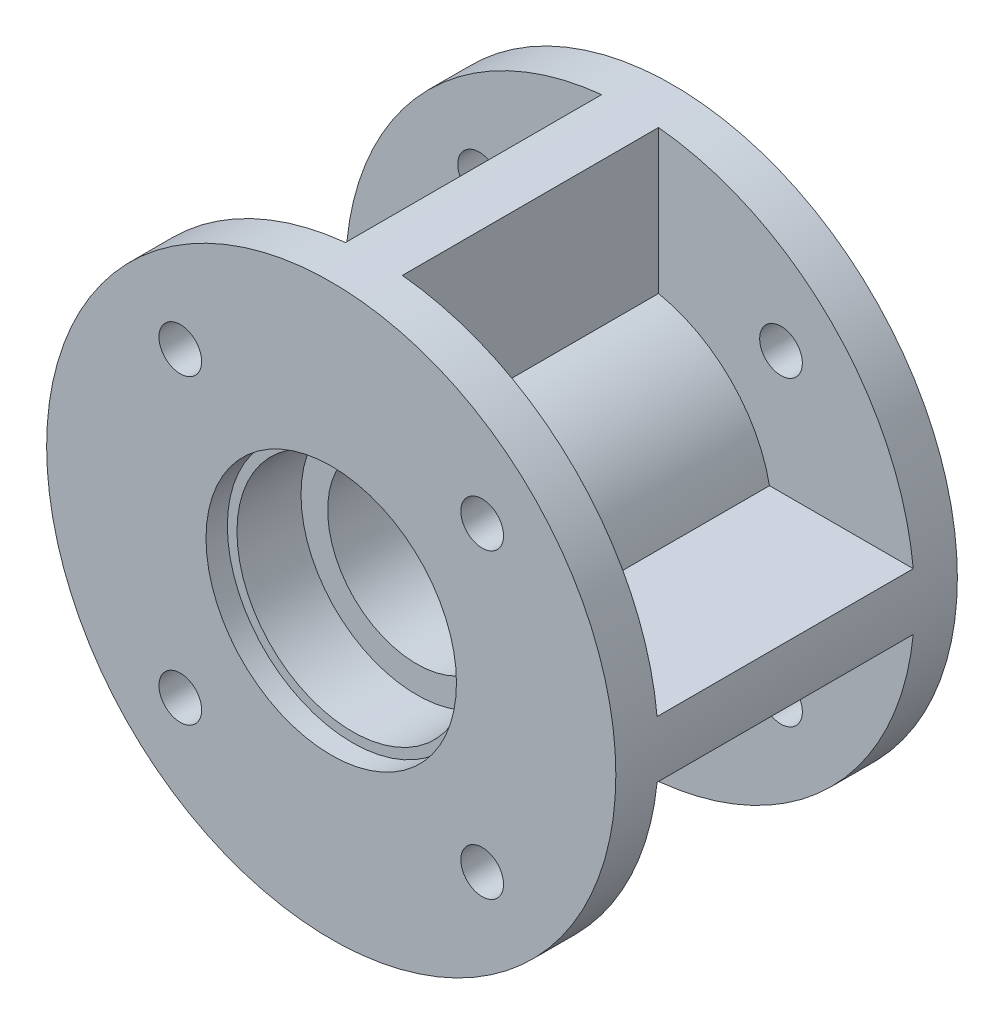
SolidWorks part; units mm, degrees
material "PLA Generic"
ref_plane "Front Plane" through (0, 0, 0) normal (0, 0, 1) x (1, 0, 0)
ref_plane "Top Plane" through (0, 0, 0) normal (0, 1, 0) x (1, 0, 0)
ref_plane "Right Plane" through (0, 0, 0) normal (1, 0, 0) x (0, 0, -1)
sketch "Sketch1" plane through (0, 0, 0) normal (0, 0, 1) x (1, 0, 0)
  circle A0 centre (0, 0) radius 12.5
  circle A1 centre (0, 0) radius 40
  dimension "D1" = 80
  dimension "D2" = 25
extrude "Boss-Extrude1" add sketch "Sketch1" along normal blind 6
sketch "Sketch2" plane through (0, 0, 6) normal (0, 0, 1) x (1, 0, 0)
  circle A0 centre (0, 0) radius 20
  circle A1 centre (0, 0) radius 12.5
  dimension "D1" = 40
extrude "Boss-Extrude2" add sketch "Sketch2" along normal blind 30
sketch "Sketch6" plane through (0, 0, 36) normal (0, 0, 1) x (1, 0, 0)
  circle A0 centre (0, 0) radius 20
  circle A1 centre (0, 0) radius 16.25
  dimension "D1" = 32.5
extrude "Boss-Extrude5" add sketch "Sketch6" along normal blind 12
sketch "Sketch8" plane through (0, 0, 6) normal (0, 0, 1) x (1, 0, 0)
  line L0 (4, -39.7995) -> (4, -19.5959)
  line L2 (39.7995, 4) -> (19.5959, 4)
  line L4 (19.5959, -4) -> (39.7995, -4)
  line L5 (20, 0) -> (40, 0) construction
  line L6 (-4, -19.5959) -> (-4, -39.7995)
  line L7 (-39.7995, -4) -> (-19.5959, -4)
  line L8 (-19.5959, 4) -> (-39.7995, 4)
  line L9 (-4, 39.7995) -> (-4, 19.5959)
  line L10 (4, 19.5959) -> (4, 39.7995)
  circle A0 centre (0, 0) radius 40 construction
  arc A1 (19.5959, -4) -> (19.5959, 4) centre (0, 0) ccw
  arc A2 (39.7995, -4) -> (39.7995, 4) centre (0, 0) ccw
  arc A3 (-4, -19.5959) -> (4, -19.5959) centre (0, 0) ccw
  arc A4 (-4, -39.7995) -> (4, -39.7995) centre (0, 0) ccw
  arc A5 (-19.5959, 4) -> (-19.5959, -4) centre (0, 0) ccw
  arc A6 (-39.7995, 4) -> (-39.7995, -4) centre (0, 0) ccw
  arc A7 (4, 19.5959) -> (-4, 19.5959) centre (0, 0) ccw
  arc A8 (4, 39.7995) -> (-4, 39.7995) centre (0, 0) ccw
  point P9 (40, 0)
  point P26 (0, 0)
  dimension "D1" = 4
extrude "Boss-Extrude6" add sketch "Sketch8" along normal up to surface (42 mm away) up to face at (20, 0, 48)
sketch "Sketch9" plane through (0, 0, 48) normal (0, 0, 1) x (1, 0, 0)
  circle A0 centre (0, 0) radius 17.6
  dimension "D1" = 35.2
extrude "Cut-Extrude1" cut sketch "Sketch9" against normal blind 3
sketch "Sketch11" plane through (0, 0, 48) normal (0, 0, 1) x (1, 0, 0)
  circle A0 centre (0, 0) radius 40
  circle A1 centre (0, 0) radius 20
extrude "Boss-Extrude14" add sketch "Sketch11" against normal blind 6 contours A0 | A1
sketch "Sketch12" plane through (0, 0, 0) normal (0, 0, -1) x (-1, 0, 0)
  line L0 (0, 0) -> (-54.2872, 0) construction
  line L1 (0, 0) -> (-21.2132, 21.2132) construction
  circle A0 centre (-21.2132, 21.2132) radius 3
  circle A1 centre (21.2132, 21.2132) radius 3
  circle A2 centre (21.2132, -21.2132) radius 3
  circle A3 centre (-21.2132, -21.2132) radius 3
  point P16 (0, 0)
  dimension "D3" = 6
  dimension "D1" = 45
  dimension "D2" = 30
  dimension "D4" = 4
extrude "Cut-Extrude2" cut sketch "Sketch12" against normal blind 78
